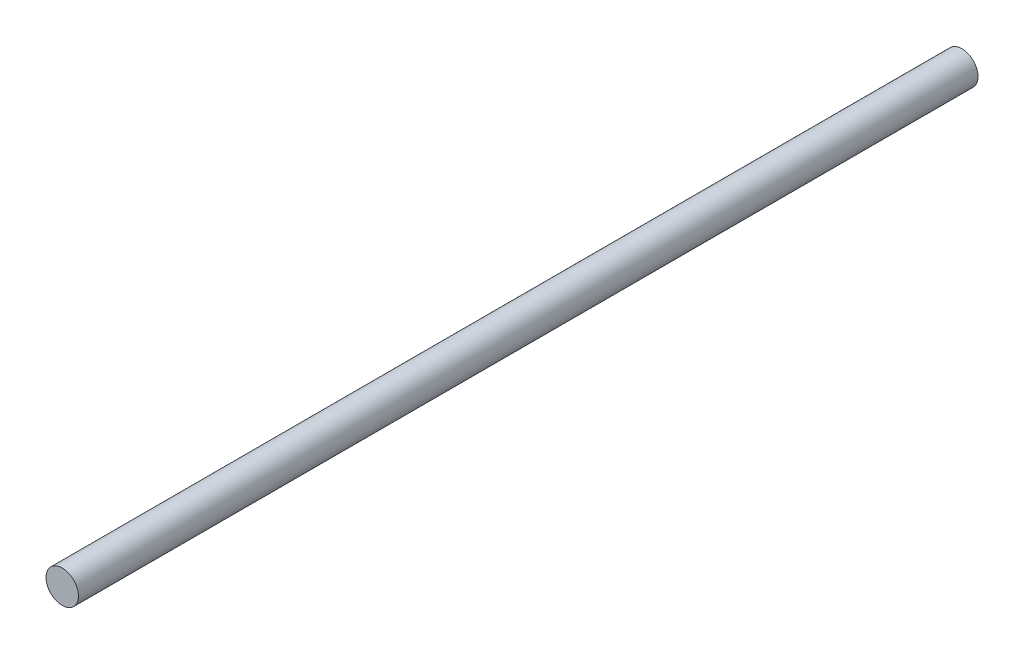
SolidWorks part; units mm, degrees
material "Stop 1060"
ref_plane "Płaszczyzna przednia" through (0, 0, 0) normal (0, 0, 1) x (1, 0, 0)
ref_plane "Płaszczyzna górna" through (0, 0, 0) normal (0, 1, 0) x (1, 0, 0)
ref_plane "Płaszczyzna prawa" through (0, 0, 0) normal (1, 0, 0) x (0, 0, -1)
sketch "Sketch1" plane through (0, 0, 0) normal (0, 0, 1) x (1, 0, 0)
  circle A0 centre (0, 0) radius 3.5
  dimension "D1" = 7
extrude "Boss-Extrude1" add sketch "Sketch1" along normal blind 194
